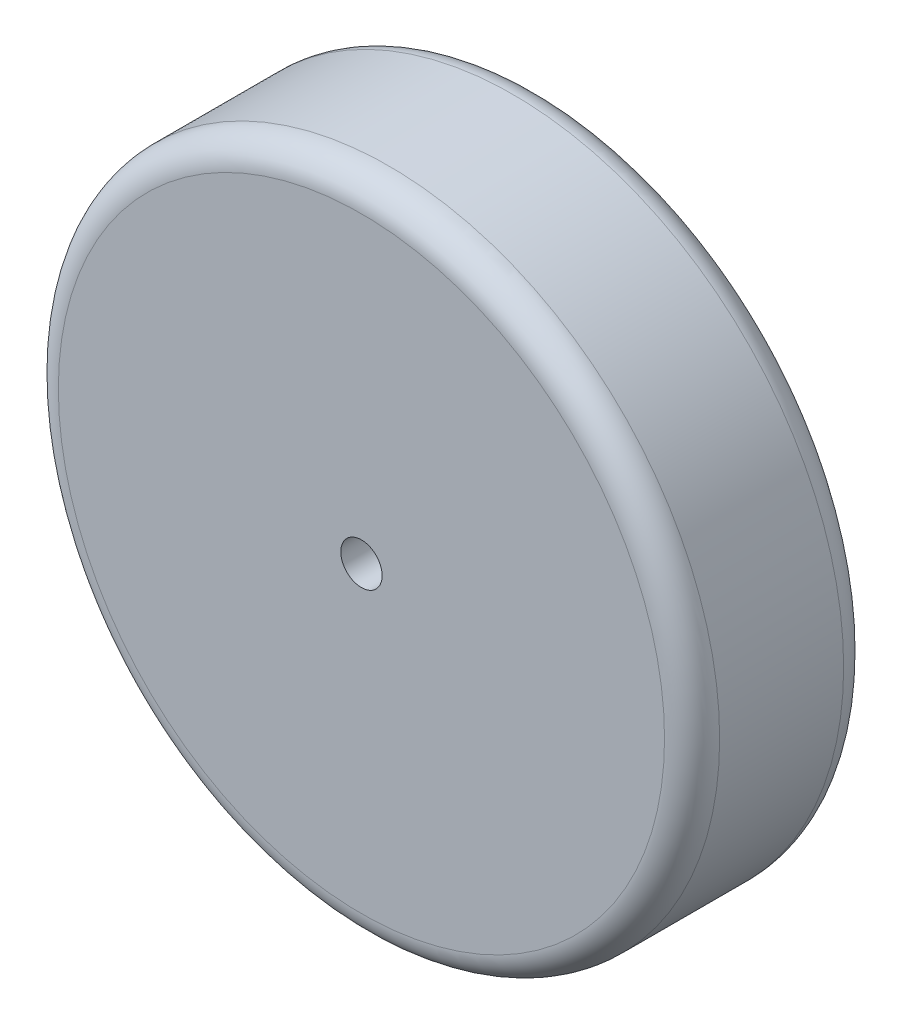
SolidWorks part; units mm, degrees
ref_plane "Alzado" through (0, 0, 0) normal (0, 0, 1) x (1, 0, 0)
ref_plane "Planta" through (0, 0, 0) normal (0, 1, 0) x (1, 0, 0)
ref_plane "Vista lateral" through (0, 0, 0) normal (1, 0, 0) x (0, 0, -1)
sketch "Croquis1" plane through (0, 0, 0) normal (0, 0, 1) x (1, 0, 0)
  circle A0 centre (-49.2426, 14.1937) radius 24
  circle A1 centre (-49.2426, 14.1937) radius 1.5
  point P3 (0, 0)
extrude "Saliente-Extruir1" add sketch "Croquis1" along normal blind 13
fillet "Redondeo1" radius 2 1 edges at (-25.2426, 14.1937, 13)
fillet "Redondeo2" radius 2 1 edges at (-25.2426, 14.1937, 0)
